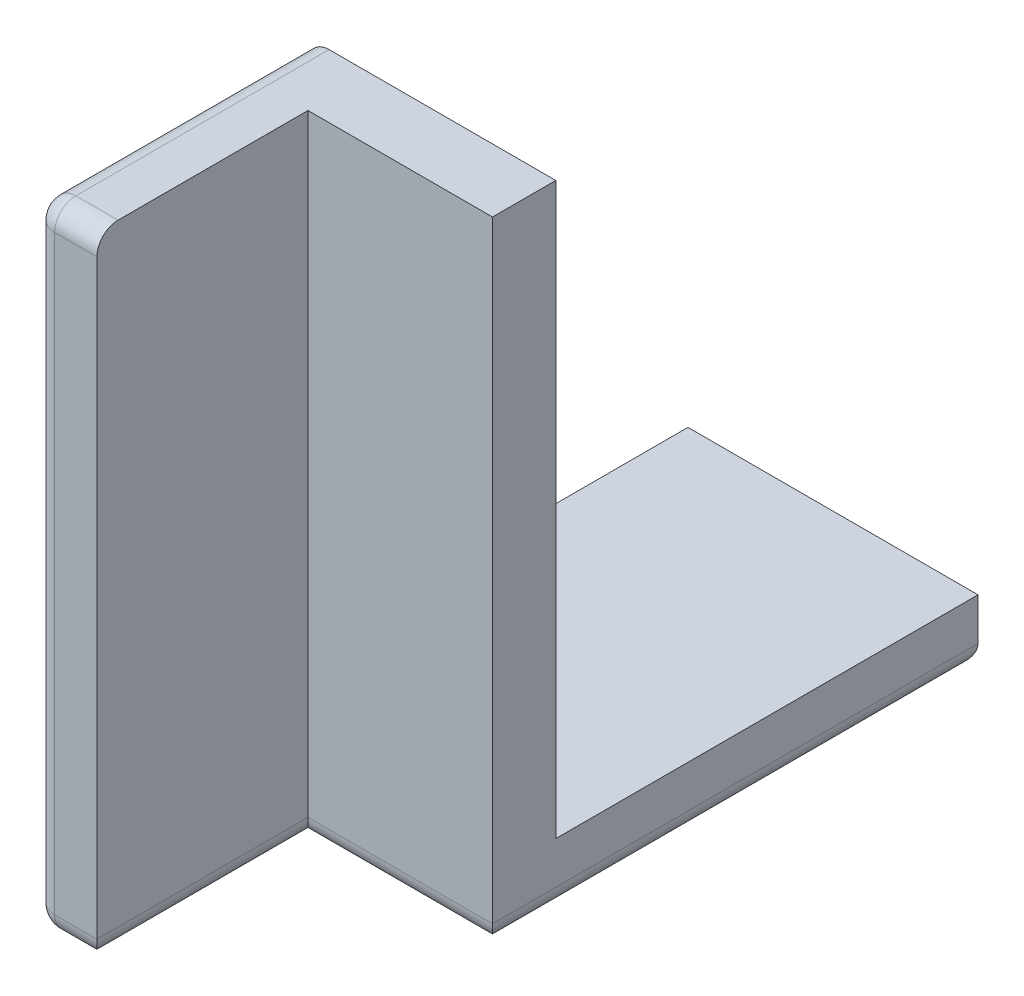
SolidWorks part; units mm, degrees
ref_plane "Front Plane" through (0, 0, 0) normal (0, 0, 1) x (1, 0, 0)
ref_plane "Top Plane" through (0, 0, 0) normal (0, 1, 0) x (1, 0, 0)
ref_plane "Right Plane" through (0, 0, 0) normal (1, 0, 0) x (0, 0, -1)
sketch "Sketch1" plane through (0, 0, 0) normal (0, 0, 1) x (1, 0, 0)
  line L0 (0, -30) -> (0, 0)
  line L3 (0, -30) -> (8.74, -30)
  line L4 (8.74, -30) -> (8.74, 0)
  line L5 (8.74, 0) -> (0, 0)
  dimension "D1" = 8.74
  dimension "D2" = 30
extrude "Boss-Extrude1" add sketch "Sketch1" along normal blind 3
sketch "Sketch8" plane through (0, 0, 0) normal (0, 0, -1) x (-1, 0, 0)
  line L0 (-8.74, -30) -> (0, -30)
  line L1 (0, -30) -> (0, -27)
  line L2 (0, 0) -> (0, -30) construction
  line L3 (0, -27) -> (-8.74, -27)
  line L4 (-8.74, -30) -> (-8.74, 0) construction
  line L5 (-8.74, -27) -> (-8.74, -30)
  dimension "D1" = 3
extrude "Boss-Extrude7" add sketch "Sketch8" along normal blind 20
sketch "Sketch9" plane through (0, 0, 0) normal (-1, 0, 0) x (0, 0, 1)
  line L0 (-20, -27) -> (0, -27)
  line L1 (0, -27) -> (0, -30)
  line L2 (3, -30) -> (-20, -30) construction
  line L3 (0, -30) -> (-20, -30)
  line L4 (-20, -30) -> (-20, -27)
extrude "Boss-Extrude8" add sketch "Sketch9" along normal blind 5
sketch "Sketch12" plane through (0, 0, 0) normal (-1, 0, 0) x (0, 0, 1)
  line L0 (0, 0) -> (0, -30)
  line L1 (0, -30) -> (3, -30)
  line L2 (3, -30) -> (3, 0)
  line L3 (3, 0) -> (0, 0)
extrude "Boss-Extrude10" add sketch "Sketch12" along normal blind 3
sketch "Sketch13" plane through (0, 0, 3) normal (0, 0, 1) x (1, 0, 0)
  line L0 (-3, 0) -> (-3, -30)
  line L1 (-3, -30) -> (0, -30)
  line L2 (-3, -30) -> (8.74, -30) construction
  line L3 (0, -30) -> (0, 0)
  line L4 (8.74, 0) -> (-3, 0) construction
  line L5 (0, 0) -> (-3, 0)
  dimension "D1" = 3
extrude "Boss-Extrude11" add sketch "Sketch13" along normal blind 10
fillet "Fillet6" radius 1 12 edges at (8.74, -30, -8.5) (1.87, -30, -20) (-5, -30, -10) (-4, -30, 0) (-3, -30, 6.5) (-1.5, -30, 13) (0, -30, 8) (4.37, -30, 3) (-5, -28.5, 0) (-3, -15, 13) (-3, 0, 6.5) (-1.5, 0, 13)
